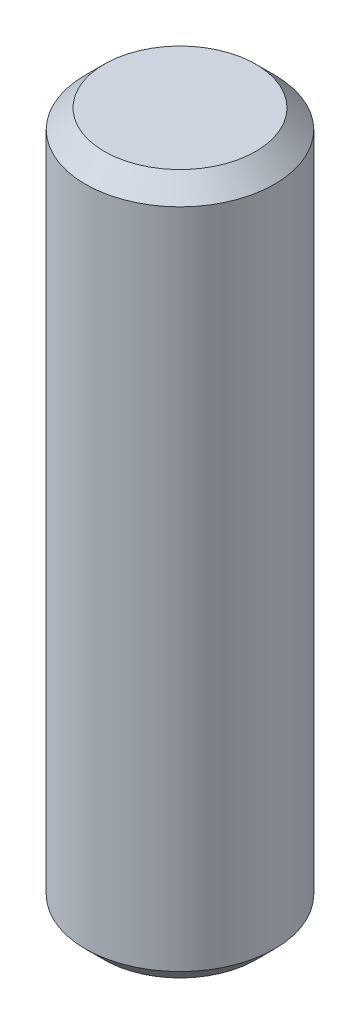
SolidWorks part; units mm, degrees
ref_plane "Front Plane" through (0, 0, 0) normal (0, 0, 1) x (1, 0, 0)
ref_plane "Top Plane" through (0, 0, 0) normal (0, 1, 0) x (1, 0, 0)
ref_plane "Right Plane" through (0, 0, 0) normal (1, 0, 0) x (0, 0, -1)
sketch "Sketch1" plane through (0, 0, 0) normal (1, 0, 0) x (0, 0, -1)
  line L1 (0, 0) -> (10, 0)
  line L2 (0, 0) -> (0, 74)
  line L3 (0, 74) -> (10, 74)
  line L4 (10, 0) -> (10, 74)
  dimension "D1" = 74
  dimension "D2" = 10
revolve "Revolve1" add sketch "Sketch1" angle 360 about L2
cosmetic thread "Cosmetic Thread1" parameters "D1"=24, "D2"=17.252
cosmetic thread "Cosmetic Thread2" parameters "D1"=24, "D2"=17.252
chamfer "Chamfer1" distance 2 angle 45 2 edges at (0, 0, -10) (0, 74, -10)
